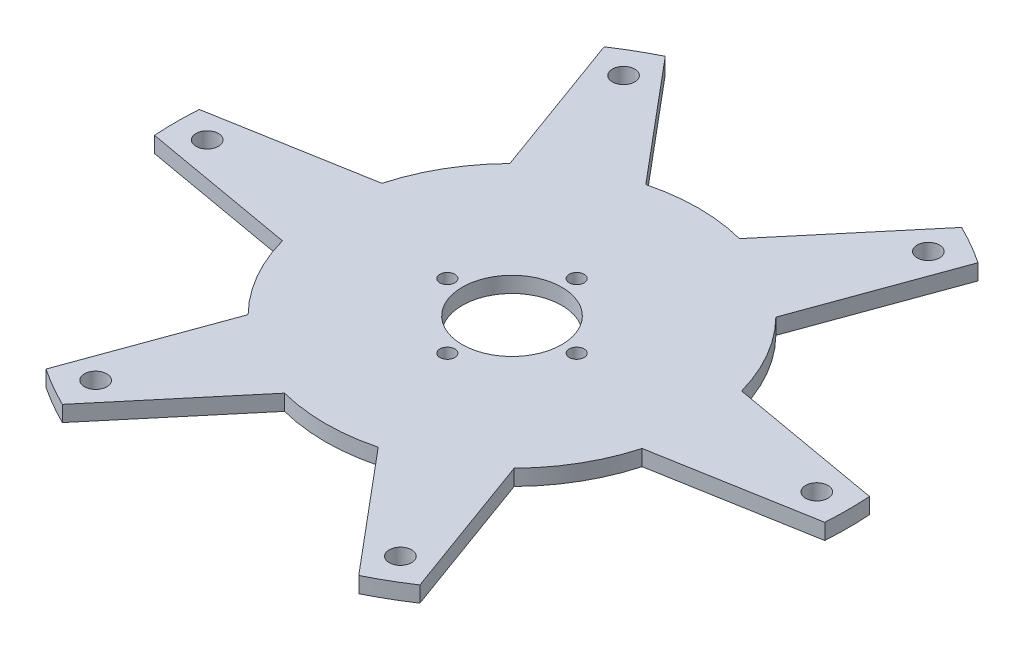
SolidWorks part; units mm, degrees
ref_plane "Front Plane" through (0, 0, 0) normal (0, 0, 1) x (1, 0, 0)
ref_plane "Top Plane" through (0, 0, 0) normal (0, 1, 0) x (1, 0, 0)
ref_plane "Right Plane" through (0, 0, 0) normal (1, 0, 0) x (0, 0, -1)
sketch "Sketch2" plane through (0, 0, 0) normal (0, 1, 0) x (1, 0, 0)
  line L0 (-55, 0) -> (-67.5, 0) construction
  line L1 (-36.1421, 10) -> (-67.35, 4.4972)
  line L2 (-36.1421, -10) -> (-67.35, -4.4972)
  line L3 (-9.4108, 36.3) -> (-29.7803, 60.5754)
  line L4 (-26.7313, 26.3) -> (-37.5697, 56.0782)
  line L5 (26.7313, 26.3) -> (37.5697, 56.0782)
  line L6 (9.4108, 36.3) -> (29.7803, 60.5754)
  line L7 (36.1421, -10) -> (67.35, -4.4972)
  line L8 (36.1421, 10) -> (67.35, 4.4972)
  line L9 (9.4108, -36.3) -> (29.7803, -60.5754)
  line L10 (26.7313, -26.3) -> (37.5697, -56.0782)
  line L11 (-26.7313, -26.3) -> (-37.5697, -56.0782)
  line L12 (-9.4108, -36.3) -> (-29.7803, -60.5754)
  circle A0 centre (0, 0) radius 10
  arc A1 (-67.35, 4.4972) -> (-67.35, -4.4972) centre (0, 0) ccw
  circle A2 centre (0, 0) radius 13 construction
  circle A3 centre (0, 13) radius 1.5
  circle A4 centre (13, 0) radius 1.5
  circle A5 centre (0, -13) radius 1.5
  circle A6 centre (-13, 0) radius 1.5
  circle A7 centre (0, 0) radius 55 construction
  circle A8 centre (-61.25, 0) radius 2.25
  circle A9 centre (-30.625, 53.0441) radius 2.25
  circle A10 centre (30.625, 53.0441) radius 2.25
  circle A11 centre (61.25, 0) radius 2.25
  circle A12 centre (30.625, -53.0441) radius 2.25
  circle A13 centre (-30.625, -53.0441) radius 2.25
  circle A14 centre (0, 0) radius 61.25 construction
  arc A15 (-36.1421, -10) -> (-26.7313, -26.3) centre (0, 0) ccw
  arc A16 (-29.7803, 60.5754) -> (-37.5697, 56.0782) centre (0, 0) ccw
  arc A17 (37.5697, 56.0782) -> (29.7803, 60.5754) centre (0, 0) ccw
  arc A18 (67.35, -4.4972) -> (67.35, 4.4972) centre (0, 0) ccw
  arc A19 (29.7803, -60.5754) -> (37.5697, -56.0782) centre (0, 0) ccw
  arc A20 (-37.5697, -56.0782) -> (-29.7803, -60.5754) centre (0, 0) ccw
  arc A21 (-9.4108, -36.3) -> (9.4108, -36.3) centre (0, 0) ccw
  arc A22 (26.7313, -26.3) -> (36.1421, -10) centre (0, 0) ccw
  arc A23 (36.1421, 10) -> (26.7313, 26.3) centre (0, 0) ccw
  arc A24 (9.4108, 36.3) -> (-9.4108, 36.3) centre (0, 0) ccw
  arc A25 (-26.7313, 26.3) -> (-36.1421, 10) centre (0, 0) ccw
  point P16 (0, 0)
  point P31 (0, 0)
  point P57 (0, 0)
  dimension "D1" = 20
  dimension "D2" = 135
  dimension "D3" = 26
  dimension "D4" = 3
  dimension "D6" = 110
  dimension "D7" = 4.5
  dimension "D9" = 75
  dimension "D10" = 10
  dimension "D11" = 20
  dimension "D5" = 4
  dimension "D8" = 6
  dimension "D12" = 6
extrude "Boss-Extrude1" add sketch "Sketch2" along normal blind 3.175
